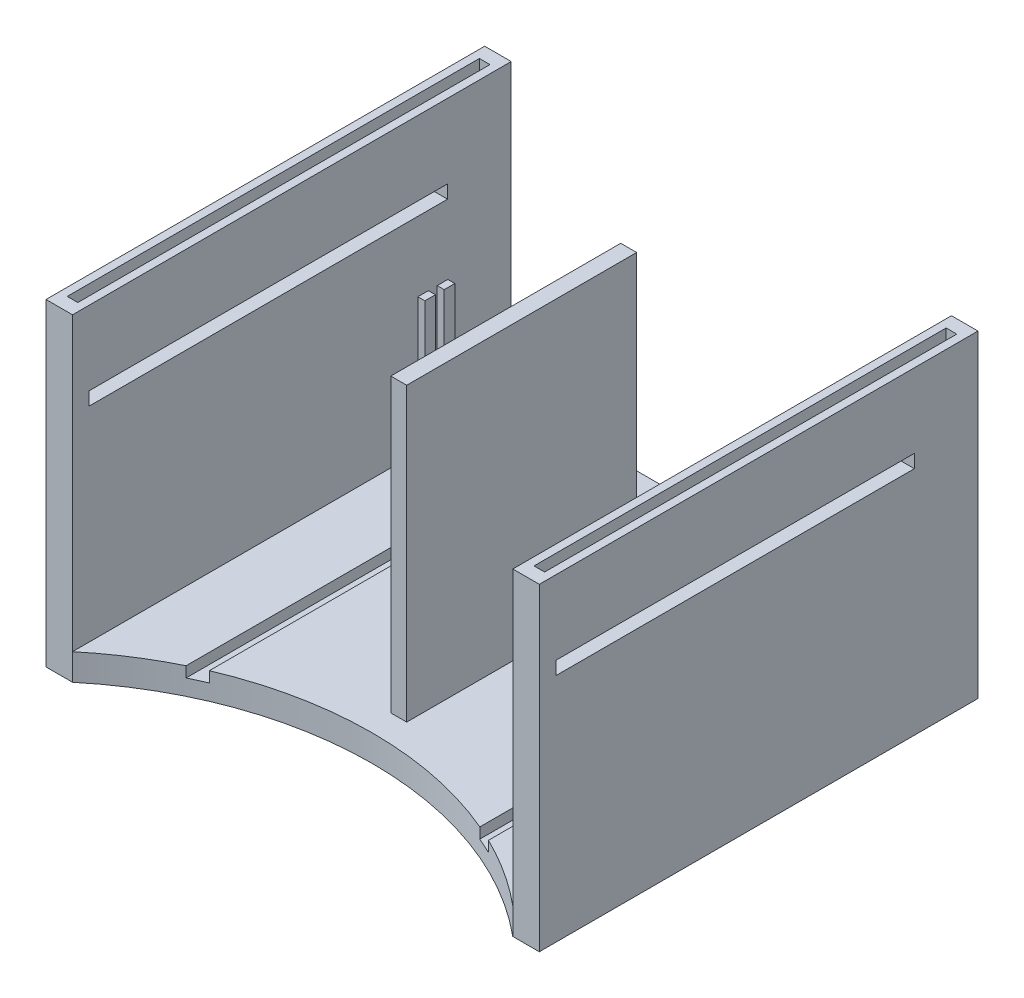
SolidWorks part; units mm, degrees
ref_plane "Front Plane" through (0, 0, 0) normal (0, 0, 1) x (1, 0, 0)
ref_plane "Top Plane" through (0, 0, 0) normal (0, 1, 0) x (1, 0, 0)
ref_plane "Right Plane" through (0, 0, 0) normal (1, 0, 0) x (0, 0, -1)
sketch "Sketch2" plane through (0, 0, 0) normal (0, 0, 1) x (1, 0, 0)
  line L0 (0, 0) -> (186, 0)
  line L1 (186, 0) -> (186, 120)
  line L2 (0, 0) -> (0, 120)
  dimension "D1" = 120
  dimension "D2" = 186
extrude "Extrude-Thin2" add sketch "Sketch2" along normal blind 165.4 thin thin type one direction wall 10
sketch "Sketch11" plane through (0, 10, 0) normal (0, 1, 0) x (1, 0, 0)
  line L0 (10, -165.4) -> (10, 0) construction
  line L1 (11.5, -32.703) -> (174.5, -32.703)
  line L2 (11.5, -32.703) -> (11.5, -36.703)
  line L3 (11.5, -36.703) -> (174.5, -36.703)
  line L4 (174.5, -32.703) -> (174.5, -36.703)
  line L6 (176, 0) -> (10, 0) construction
  dimension "D1" = 32.703
  dimension "D2" = 4
  dimension "D3" = 163
  dimension "D4" = 1.5
extrude "Boss-Extrude3" add sketch "Sketch11" along normal blind 2.6416
sketch "Sketch13" plane through (10, 0, 0) normal (1, 0, 0) x (0, 0, -1)
  line L0 (0, 120) -> (0, 0) construction
  line L1 (-159.195, 92.0516) -> (-24, 92.0516)
  line L2 (-159.195, 92.0516) -> (-159.195, 87.0516)
  line L3 (-159.195, 87.0516) -> (-24, 87.0516)
  line L4 (-24, 92.0516) -> (-24, 87.0516)
  line L6 (-165.4, 120) -> (-165.4, 0) construction
  line L7 (-165.4, 120) -> (0, 120) construction
  dimension "D1" = 5
  dimension "D2" = 6.205
  dimension "D3" = 24
  dimension "D4" = 27.9484
extrude "Cut-Extrude6" cut sketch "Sketch13" against normal through all both and the other way through all
sketch "Sketch14" plane through (0, 10, 0) normal (0, 1, 0) x (1, 0, 0)
  line L0 (176, -165.4) -> (10, -165.4)
  line L1 (93, -135.4) -> (10, -135.4) construction
  line L2 (10, -165.4) -> (10, 0) construction
  arc A0 (10, -165.4) -> (176, -165.4) centre (93, -265.2167) cw
  dimension "D1" = 30
extrude "Cut-Extrude7" cut sketch "Sketch14" against normal through all
sketch "Sketch19" plane through (0, 120, 0) normal (0, 1, 0) x (1, 0, 0)
  line L0 (10, -165.4) -> (10, 0) construction
  line L1 (3, -5) -> (7, -5)
  line L2 (3, -5) -> (3, -160.4)
  line L3 (3, -160.4) -> (7, -160.4)
  line L4 (7, -5) -> (7, -160.4)
  line L5 (0, -165.4) -> (0, 0) construction
  line L6 (0, 0) -> (10, 0) construction
  line L7 (0, -165.4) -> (10, -165.4) construction
  point P9 (5, 0)
  point P12 (5, -165.4)
  dimension "D1" = 3
  dimension "D2" = 3
  dimension "D3" = 5
  dimension "D4" = 5
extrude "Cut-Extrude9" cut sketch "Sketch19" against normal blind 10
sketch "Sketch20" plane through (0, 120, 0) normal (0, 1, 0) x (1, 0, 0)
  line L0 (186, -165.4) -> (186, 0) construction
  line L1 (179, -5) -> (183, -5)
  line L2 (179, -5) -> (179, -160.4)
  line L3 (179, -160.4) -> (183, -160.4)
  line L4 (183, -5) -> (183, -160.4)
  line L5 (176, -165.4) -> (176, 0) construction
  line L6 (176, 0) -> (186, 0) construction
  line L7 (176, -165.4) -> (186, -165.4) construction
  point P9 (181, 0)
  point P12 (181, -165.4)
  dimension "D1" = 3
  dimension "D2" = 3
  dimension "D3" = 5
  dimension "D4" = 5
extrude "Cut-Extrude10" cut sketch "Sketch20" against normal blind 10
sketch "Sketch21" plane through (0, 10, 0) normal (0, 1, 0) x (1, 0, 0)
  line L0 (176, -165.4) -> (176, 0) construction
  line L1 (90, -38.703) -> (96, -38.703)
  line L2 (90, -38.703) -> (90, -125.4)
  line L3 (90, -125.4) -> (96, -125.4)
  line L4 (96, -38.703) -> (96, -125.4)
  line L5 (10, -165.4) -> (10, 0) construction
  line L7 (10, -159.195) -> (10, -24) construction
  line L8 (10, -119.195) -> (176, -119.195) construction
  line L9 (10, -165.4) -> (10, 0) construction
  line L10 (0, -165.4) -> (10, -165.4) construction
  line L11 (11.5, -36.703) -> (174.5, -36.703) construction
  dimension "D1" = 80
  dimension "D2" = 80
  dimension "D3" = 40
  dimension "D4" = 46.205
  dimension "D5" = 2
extrude "Boss-Extrude4" add sketch "Sketch21" along direction (0, 1, 0) on the side of the normal through all
sketch "Sketch22" plane through (0, 10, 0) normal (0, 1, 0) x (1, 0, 0)
  line L0 (36, -51.703) -> (36, -148.5832)
  line L1 (36, -148.5832) -> (42, -145.8376)
  line L2 (42, -145.8376) -> (42, -51.703)
  line L3 (42, -51.703) -> (36, -51.703)
  line L4 (11.5, -36.703) -> (174.5, -36.703) construction
  line L6 (10, -159.195) -> (10, -24) construction
  line L7 (144, -145.8376) -> (150, -148.5832)
  line L8 (150, -148.5832) -> (150, -51.703)
  line L9 (150, -51.703) -> (144, -51.703)
  line L10 (144, -51.703) -> (144, -145.8376)
  line L11 (176, -165.4) -> (176, 0) construction
  arc A0 (176, -165.4) -> (10, -165.4) centre (93, -265.2167) ccw construction
  dimension "D1" = 6
  dimension "D2" = 26
  dimension "D3" = 6
  dimension "D4" = 26
  dimension "D5" = 15
extrude "Cut-Extrude11" cut sketch "Sketch22" against normal blind 4
sketch "Sketch23" plane through (0, 10, 0) normal (0, 1, 0) x (1, 0, 0)
  line L0 (10, -165.4) -> (10, 0) construction
  line L1 (11.5, -25.4) -> (174.5, -25.4)
  line L2 (11.5, -25.4) -> (11.5, -29.4)
  line L3 (11.5, -29.4) -> (174.5, -29.4)
  line L4 (174.5, -25.4) -> (174.5, -29.4)
  line L5 (176, -165.4) -> (176, 0) construction
  line L8 (174.5, -32.703) -> (11.5, -32.703) construction
  dimension "D1" = 3.303
  dimension "D2" = 1.5
  dimension "D3" = 1.5
  dimension "D4" = 4
extrude "Boss-Extrude5" add sketch "Sketch23" along normal blind 2.6416
sketch "Sketch24" plane through (0, 12.6416, 0) normal (0, 1, 0) x (1, 0, 0)
  line L0 (11.5, -36.703) -> (174.5, -36.703) construction
  line L1 (11.5, -32.703) -> (14.1416, -32.703)
  line L2 (11.5, -32.703) -> (11.5, -36.703)
  line L3 (11.5, -36.703) -> (14.1416, -36.703)
  line L4 (14.1416, -32.703) -> (14.1416, -36.703)
  dimension "D1" = 2.6416
extrude "Boss-Extrude6" add sketch "Sketch24" along normal blind 49.6416
sketch "Sketch25" plane through (0, 12.6416, 0) normal (0, 1, 0) x (1, 0, 0)
  line L0 (11.5, -29.4) -> (174.5, -29.4) construction
  line L1 (11.5, -25.4) -> (14.14, -25.4)
  line L2 (11.5, -25.4) -> (11.5, -29.4)
  line L3 (11.5, -29.4) -> (14.14, -29.4)
  line L4 (14.14, -25.4) -> (14.14, -29.4)
  dimension "D1" = 2.64
extrude "Boss-Extrude7" add sketch "Sketch25" along normal blind 49.6416
sketch "Sketch26" plane through (0, 12.6416, 0) normal (0, 1, 0) x (1, 0, 0)
  line L0 (14.1416, -36.703) -> (174.5, -36.703) construction
  line L1 (174.5, -32.703) -> (171.86, -32.703)
  line L2 (174.5, -32.703) -> (174.5, -36.703)
  line L3 (174.5, -36.703) -> (171.86, -36.703)
  line L4 (171.86, -32.703) -> (171.86, -36.703)
  line L5 (174.5, -29.4) -> (174.5, -25.4) construction
  line L6 (174.5, -25.4) -> (171.86, -25.4)
  line L7 (174.5, -25.4) -> (174.5, -29.4)
  line L8 (174.5, -29.4) -> (171.86, -29.4)
  line L9 (171.86, -25.4) -> (171.86, -29.4)
  line L10 (174.5, -29.4) -> (174.5, -25.4) construction
  line L11 (14.14, -29.4) -> (174.5, -29.4) construction
  dimension "D1" = 2.64
  dimension "D2" = 2.64
extrude "Boss-Extrude8" add sketch "Sketch26" along normal blind 49.6416
